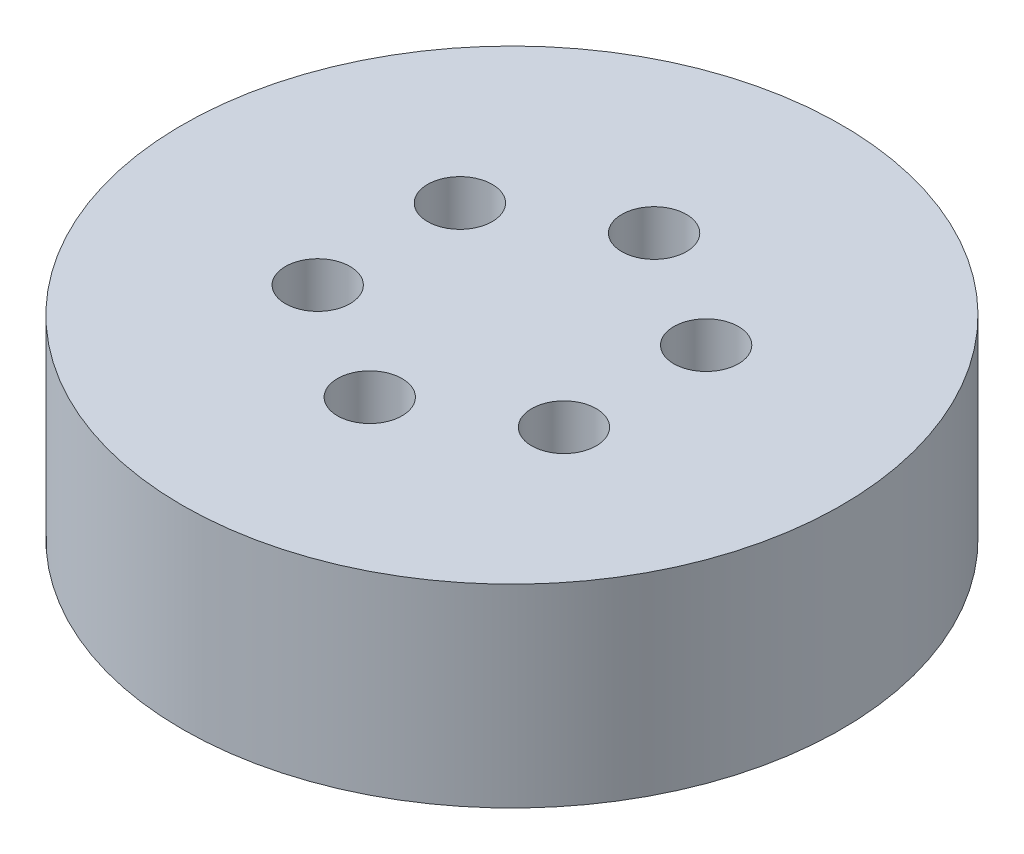
SolidWorks part; units mm, degrees
ref_plane "前视基准面" through (0, 0, 0) normal (0, 0, 1) x (1, 0, 0)
ref_plane "上视基准面" through (0, 0, 0) normal (0, 1, 0) x (1, 0, 0)
ref_plane "右视基准面" through (0, 0, 0) normal (1, 0, 0) x (0, 0, -1)
sketch "草图1" plane through (0, 0, 0) normal (0, 1, 0) x (1, 0, 0)
  line L1 (0, -11) -> (9.5263, -5.5) construction
  line L2 (9.5263, -5.5) -> (9.5263, 5.5) construction
  line L3 (9.5263, 5.5) -> (0, 11) construction
  line L4 (0, 11) -> (-9.5263, 5.5) construction
  line L5 (-9.5263, 5.5) -> (-9.5263, -5.5) construction
  line L6 (-9.5263, -5.5) -> (0, -11) construction
  circle A0 centre (0, 0) radius 25.5
  circle A1 centre (0, 0) radius 11 construction
  circle A2 centre (0, 0) radius 9.5263 construction
  circle A3 centre (0, 11) radius 2.5
  circle A4 centre (9.5263, 5.5) radius 2.5
  circle A5 centre (9.5263, -5.5) radius 2.5
  circle A6 centre (0, -11) radius 2.5
  circle A7 centre (-9.5263, -5.5) radius 2.5
  circle A8 centre (-9.5263, 5.5) radius 2.5
  dimension "D1" = 22
  dimension "D2" = 51
  dimension "D3" = 5
extrude "凸台-拉伸1" add sketch "草图1" along normal blind 15
sketch "草图3" plane through (0, 15, 0) normal (0, 1, 0) x (1, 0, 0)
  line L0 (0, 0) -> (0, 11) construction
  line L1 (0, 0) -> (-9.5263, 5.5) construction
  circle A19 centre (-9.5263, 5.5) radius 4 construction
  circle A20 centre (0, 11) radius 4 construction
  circle A21 centre (0, 11) radius 2.5 construction
  arc A22 (0, 7) -> (-2.1498, 7.6268) centre (0, 11) cw
  arc A23 (-6.0622, 3.5) -> (-5.5301, 5.6752) centre (-9.5263, 5.5) ccw
  arc A24 (-2.1498, 7.6268) -> (-5.5301, 5.6752) centre (-3.3322, 5.7716) ccw
  arc A25 (6.0622, 3.5) -> (5.5301, 5.6752) centre (9.5263, 5.5) cw
  arc A26 (5.5301, 5.6752) -> (2.1498, 7.6268) centre (3.3322, 5.7716) ccw
  arc A27 (0, 7) -> (2.1498, 7.6268) centre (0, 11) ccw
  arc A28 (6.0622, -3.5) -> (7.6799, -1.9516) centre (9.5263, -5.5) cw
  arc A29 (7.6799, -1.9516) -> (7.6799, 1.9516) centre (6.6645, 0) ccw
  arc A30 (6.0622, 3.5) -> (7.6799, 1.9516) centre (9.5263, 5.5) ccw
  arc A31 (0, -7) -> (2.1498, -7.6268) centre (0, -11) cw
  arc A32 (2.1498, -7.6268) -> (5.5301, -5.6752) centre (3.3322, -5.7716) ccw
  arc A33 (6.0622, -3.5) -> (5.5301, -5.6752) centre (9.5263, -5.5) ccw
  arc A34 (-6.0622, -3.5) -> (-5.5301, -5.6752) centre (-9.5263, -5.5) cw
  arc A35 (-5.5301, -5.6752) -> (-2.1498, -7.6268) centre (-3.3322, -5.7716) ccw
  arc A36 (0, -7) -> (-2.1498, -7.6268) centre (0, -11) ccw
  arc A37 (-6.0622, 3.5) -> (-7.6799, 1.9516) centre (-9.5263, 5.5) cw
  arc A38 (-7.6799, 1.9516) -> (-7.6799, -1.9516) centre (-6.6645, 0) ccw
  arc A39 (-6.0622, -3.5) -> (-7.6799, -1.9516) centre (-9.5263, -5.5) ccw
  point P53 (0, 0)
  dimension "D1" = 8
  dimension "D2" = 2.2
  dimension "D3" = 6
